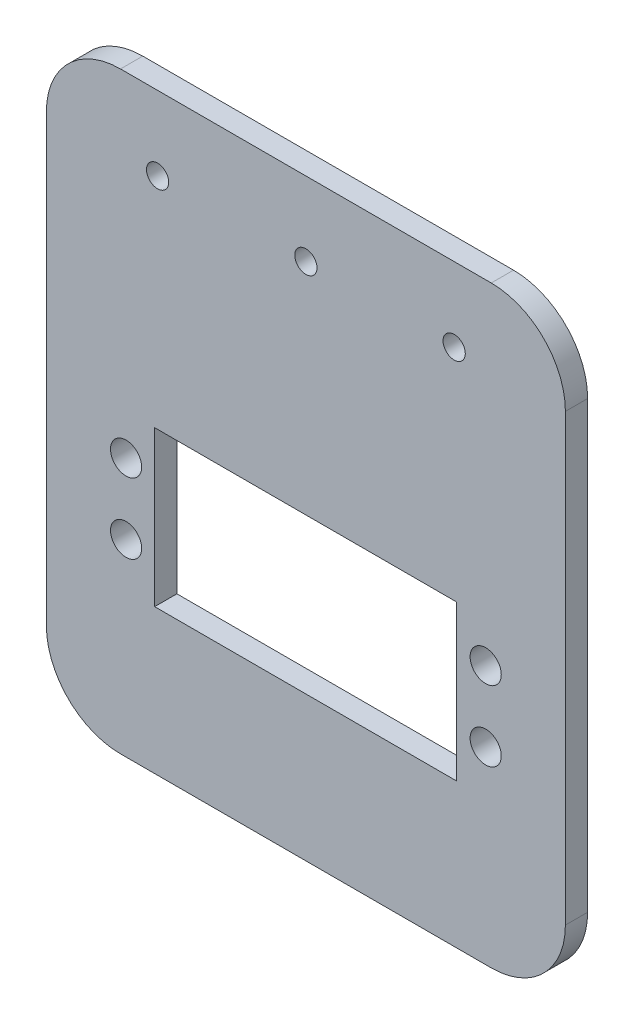
SolidWorks part; units mm, degrees
ref_plane "前视基准面" through (0, 0, 0) normal (0, 0, 1) x (1, 0, 0)
ref_plane "上视基准面" through (0, 0, 0) normal (0, 1, 0) x (1, 0, 0)
ref_plane "右视基准面" through (0, 0, 0) normal (1, 0, 0) x (0, 0, -1)
sketch "草图1" plane through (0, 0, 0) normal (0, 0, 1) x (1, 0, 0)
  line L1 (-35, 40) -> (35, 40)
  line L2 (-35, 40) -> (-35, -40)
  line L3 (-35, -40) -> (35, -40)
  line L4 (35, 40) -> (35, -40)
  line L5 (-35, 40) -> (35, -40) construction
  line L6 (-35, -40) -> (35, 40) construction
  point P0 (0, 0)
  dimension "D1" = 70
  dimension "D2" = 80
extrude "凸台-拉伸1" add sketch "草图1" along normal blind 3
sketch "草图4" plane through (0, 0, 0) normal (0, 0, -1) x (-1, 0, 0)
  line L1 (-20.2836, 0.4041) -> (20.3933, 0.4041)
  line L2 (-20.2836, 0.4041) -> (-20.2836, -20.5029)
  line L3 (-20.2836, -20.5029) -> (20.3933, -20.5029)
  line L4 (20.3933, 0.4041) -> (20.3933, -20.5029)
  circle A0 centre (24.25, -14.575) radius 2.1
  circle A1 centre (24.25, -5.075) radius 2.1
  circle A2 centre (-24.25, -14.575) radius 2.1
  circle A3 centre (-24.25, -5.075) radius 2.1
extrude "切除-拉伸3" cut sketch "草图4" against normal blind 10
sketch "草图5" plane through (0, 0, 3) normal (0, 0, 1) x (1, 0, 0)
  line L0 (35, 40) -> (-35, 40) construction
  line L1 (35, -40) -> (35, 40) construction
  line L2 (-35, 40) -> (-35, -40) construction
  circle A0 centre (-20, 30) radius 1.5
  circle A1 centre (0, 30) radius 1.5
  circle A2 centre (20, 30) radius 1.5
  dimension "D1" = 3
  dimension "D2" = 3
  dimension "D3" = 3
  dimension "D4" = 10
  dimension "D5" = 15
  dimension "D6" = 15
extrude "切除-拉伸4" cut sketch "草图5" against normal blind 10
fillet "圆角1" radius 10 4 edges at (35, -40, 1.5) (-35, -40, 1.5) (-35, 40, 1.5) (35, 40, 1.5)
